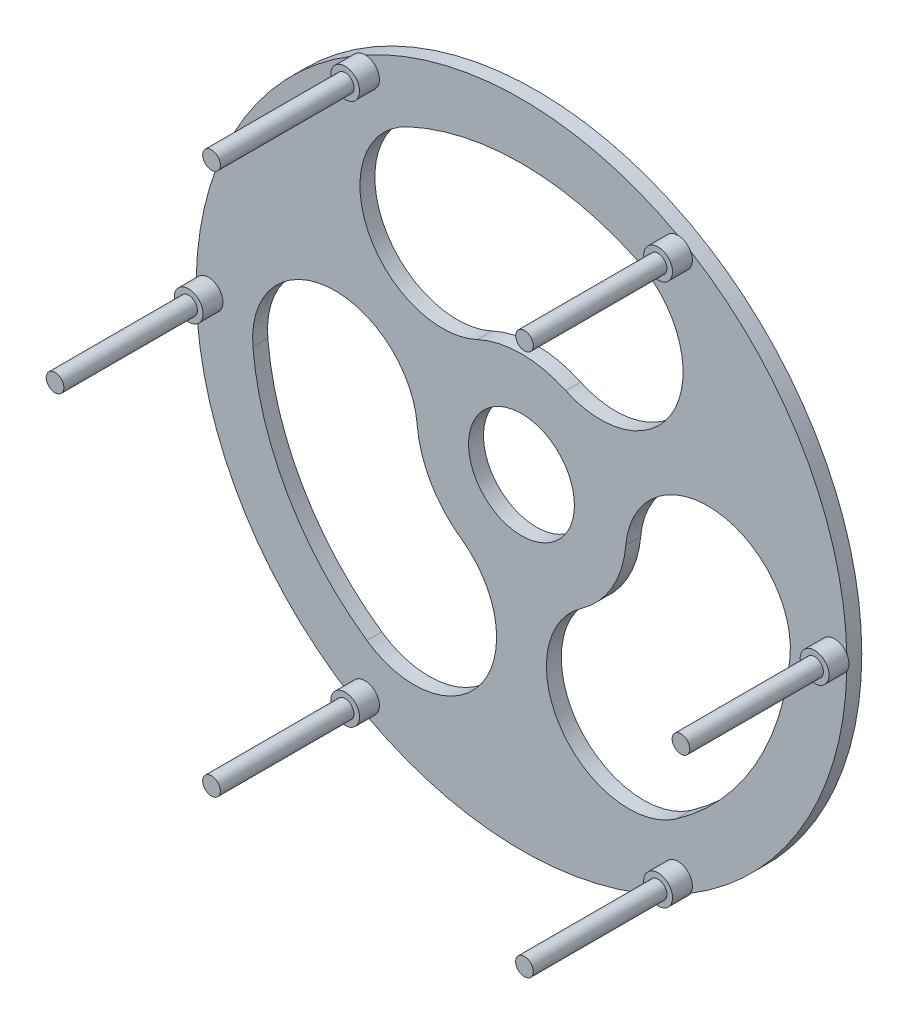
SolidWorks part; units mm, degrees
ref_plane "前视基准面" through (0, 0, 0) normal (0, 0, 1) x (1, 0, 0)
ref_plane "上视基准面" through (0, 0, 0) normal (0, 1, 0) x (1, 0, 0)
ref_plane "右视基准面" through (0, 0, 0) normal (1, 0, 0) x (0, 0, -1)
other "Configuration Table"
sketch "草图1" plane through (0, 0, 0) normal (0, 0, 1) x (1, 0, 0)
  circle A0 centre (0, 0) radius 65.5
  point P0 (0, 0)
  point P19 (0, 0)
  dimension "D1" = 131
extrude "凸台-拉伸1" add sketch "草图1" against normal blind 3 contours A0
sketch "草图2" plane through (0, 0, 0) normal (0, 0, 1) x (1, 0, 0)
  line L0 (0, 0) -> (-63, 0) construction
  circle A1 centre (-63, 0) radius 2.9
  circle A2 centre (-31.5, 54.5596) radius 2.9
  circle A3 centre (31.5, 54.5596) radius 2.9
  circle A4 centre (63, 0) radius 2.9
  circle A5 centre (31.5, -54.5596) radius 2.9
  circle A6 centre (-31.5, -54.5596) radius 2.9
  point P17 (0, 0)
  dimension "D1" = 5.8
  dimension "D2" = 63
  dimension "D3" = 6
extrude "凸台-拉伸2" add sketch "草图2" along normal blind 4 contours A2 | A3 | A1 | A6 | A5 | A4
sketch "草图3" plane through (0, 0, 0) normal (0, 0, 1) x (1, 0, 0)
  circle A0 centre (0, 0) radius 10.65
  dimension "D1" = 21.3
extrude "切除-拉伸1" cut sketch "草图3" against normal through all
sketch "草图4" plane through (0, 0, 4) normal (0, 0, 1) x (1, 0, 0)
  circle A0 centre (-31.5, 54.5596) radius 1.7772
  circle A1 centre (31.5, 54.5596) radius 1.7772
  circle A2 centre (63, 0) radius 1.7772
  circle A3 centre (31.5, -54.5596) radius 1.7772
  circle A4 centre (-31.5, -54.5596) radius 1.7772
  circle A5 centre (-63, 0) radius 1.7772
  circle A6 centre (-31.5, 54.5596) radius 2.9 construction
  point P3 (0, 0)
  point P16 (0, 0)
  dimension "D2" = 3.5544
  dimension "D1" = 6
extrude "凸台-拉伸3" add sketch "草图4" along normal blind 26.9
sketch "草图5" plane through (0, 0, 0) normal (0, 0, 1) x (1, 0, 0)
  line L0 (0, 0) -> (-15.9206, 34.1419) construction
  line L2 (15.9206, 34.1419) -> (0, 0) construction
  arc A0 (15.9206, 34.1419) -> (-15.9206, 34.1419) centre (0, 0) ccw construction
  arc A1 (22.9361, 49.1867) -> (-22.9361, 49.1867) centre (0, 0) ccw
  arc A2 (8.9051, 19.0971) -> (-8.9051, 19.0971) centre (0, 0) ccw
  arc A3 (8.9051, 19.0971) -> (22.9361, 49.1867) centre (15.9206, 34.1419) ccw
  arc A4 (-22.9361, 49.1867) -> (-8.9051, 19.0971) centre (-15.9206, 34.1419) ccw
  arc A5 (12.086, -17.2606) -> (20.9911, -1.8365) centre (0, 0) ccw
  arc A6 (12.086, -17.2606) -> (31.1289, -44.4566) centre (21.6074, -30.8586) ccw
  arc A7 (54.065, -4.7301) -> (20.9911, -1.8365) centre (37.5281, -3.2833) ccw
  arc A8 (31.1289, -44.4566) -> (54.065, -4.7301) centre (0, 0) ccw
  arc A9 (21.6074, -30.8586) -> (37.5281, -3.2833) centre (0, 0) ccw construction
  arc A10 (-20.9911, -1.8365) -> (-12.086, -17.2606) centre (0, 0) ccw
  arc A11 (-20.9911, -1.8365) -> (-54.065, -4.7301) centre (-37.5281, -3.2833) ccw
  arc A12 (-31.1289, -44.4566) -> (-12.086, -17.2606) centre (-21.6074, -30.8586) ccw
  arc A13 (-54.065, -4.7301) -> (-31.1289, -44.4566) centre (0, 0) ccw
  arc A14 (-37.5281, -3.2833) -> (-21.6074, -30.8586) centre (0, 0) ccw construction
  point P4 (0, 37.6714)
  point P17 (32.6244, -18.8357)
  point P24 (-32.6244, -18.8357)
  point P29 (0, 0)
  dimension "D1" = 50
  dimension "D2" = 3
extrude "切除-拉伸2" cut sketch "草图5" against normal through all
